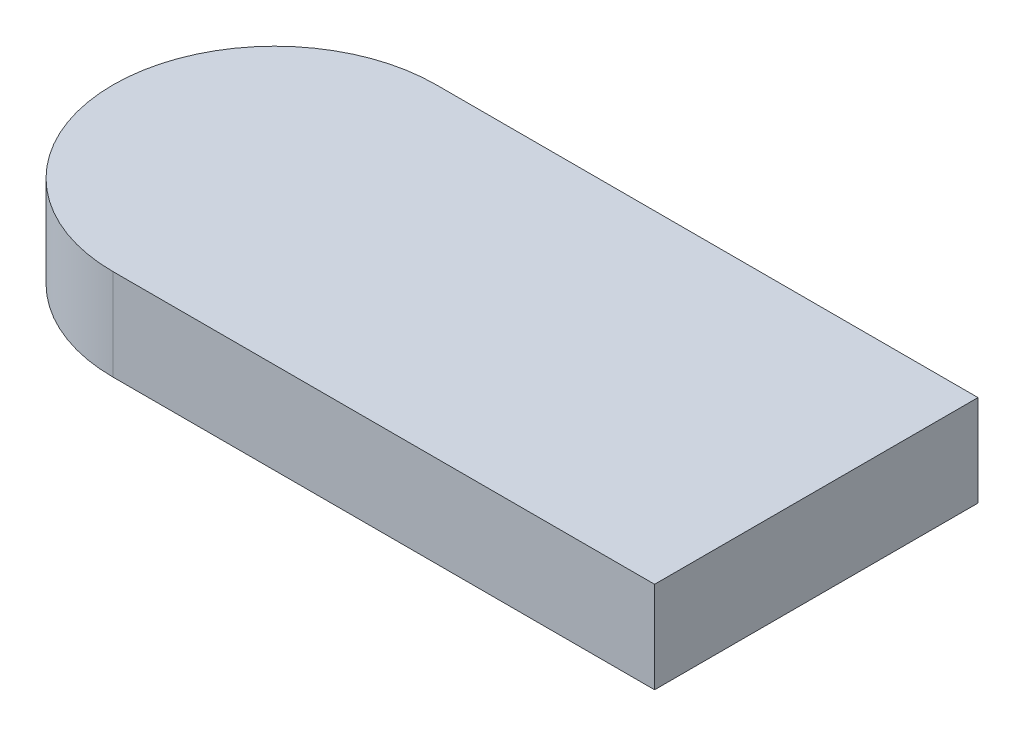
SolidWorks part; units mm, degrees
ref_plane "Front Plane" through (0, 0, 0) normal (0, 0, 1) x (1, 0, 0)
ref_plane "Top Plane" through (0, 0, 0) normal (0, 1, 0) x (1, 0, 0)
ref_plane "Right Plane" through (0, 0, 0) normal (1, 0, 0) x (0, 0, -1)
sketch "Sketch1" plane through (0, 0, 0) normal (0, 1, 0) x (1, 0, 0)
  line L1 (-53.7678, 10.8378) -> (20.2722, 10.8378)
  line L2 (-53.7678, 10.8378) -> (-53.7678, -29.1622)
  line L3 (-53.7678, -29.1622) -> (20.2722, -29.1622)
  line L4 (20.2722, 10.8378) -> (20.2722, -29.1622)
  circle A0 centre (-53.7678, -9.1622) radius 20
extrude "Boss-Extrude1" add sketch "Sketch1" along normal blind 3 contours A0 L3 L4 L1 | L2 A0 | L2 A0
sketch "Sketch2" plane through (0, 3, 0) normal (0, 1, 0) x (1, 0, 0)
  line L0 (-53.7678, 10.8378) -> (-53.7678, 13.8378)
  line L1 (-53.7678, 13.8378) -> (23.2722, 13.8378)
  line L2 (23.2722, 13.8378) -> (23.2722, -32.1622)
  line L3 (23.2722, -32.1622) -> (-53.7678, -32.1622)
  line L4 (-53.7678, -32.1622) -> (-53.7678, -29.1622)
  line L5 (20.2722, 10.8378) -> (20.2722, -29.1622) construction
  line L6 (-53.7678, 10.8378) -> (-53.7678, -29.1622)
  line L8 (-53.7678, 10.8378) -> (20.2722, 10.8378)
  line L9 (-53.7678, 10.8378) -> (-53.7678, -29.1622)
  line L10 (-53.7678, -29.1622) -> (20.2722, -29.1622)
  line L11 (20.2722, 10.8378) -> (20.2722, -29.1622)
  arc A0 (-53.7678, 10.8378) -> (-53.7678, -29.1622) centre (-53.7678, -9.1622) ccw construction
  circle A1 centre (-53.7678, -9.1622) radius 23
  circle A2 centre (-53.7678, -9.1622) radius 20
  line M3 (20.2722, 10.8378) -> (-53.7678, 10.8378)
  arc M4 (-53.7678, 10.8378) -> (-53.7678, -29.1622) centre (-53.7678, -9.1622) ccw
  line M5 (-53.7678, -29.1622) -> (20.2722, -29.1622)
  line M6 (20.2722, -29.1622) -> (20.2722, 10.8378)
  dimension "D1" = 3
extrude "Boss-Extrude3" add sketch "Sketch2" against normal blind 15 contours L0 A1 L4 M4 | L8 A1 L0 | L4 A1 M5 | A1 L3 L2 L1 L10 M3 M6
chamfer "Chamfer2" distance 2 angle 56 4 edges at (-15.2478, -12, 32.1622) (-76.7678, -12, 9.1622) (-15.2478, -12, -13.8378) (23.2722, -12, 9.1622)
